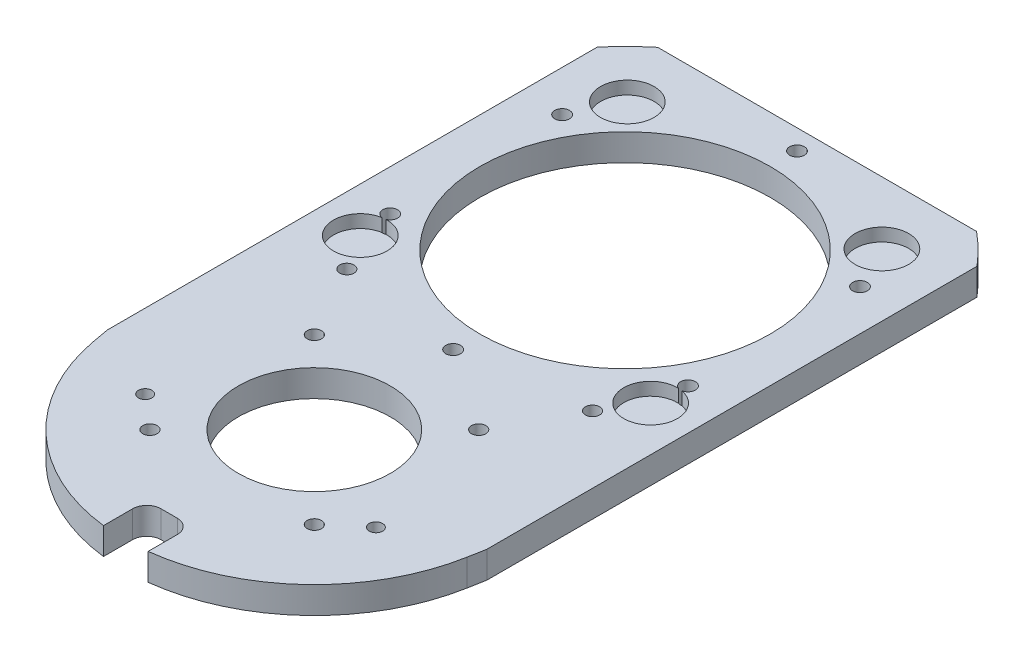
SolidWorks part; units mm, degrees
ref_plane "Front Plane" through (0, 0, 0) normal (0, 0, 1) x (1, 0, 0)
ref_plane "Top Plane" through (0, 0, 0) normal (0, 1, 0) x (1, 0, 0)
ref_plane "Right Plane" through (0, 0, 0) normal (1, 0, 0) x (0, 0, -1)
sketch "Sketch1" plane through (0, 0, 0) normal (0, 1, 0) x (1, 0, 0)
  line L0 (0, 0) -> (0, -69.5691) construction
  line L1 (0, 0) -> (0, -69.5691) construction
  line L2 (-42.5, -73.412) -> (-41.8107, -77.1925)
  line L3 (42.5, -73.412) -> (41.8107, -77.1925)
  line L4 (42.5, 36.2892) -> (42.5, -73.412)
  line L5 (-22.5, -47.0691) -> (22.5, -47.0691) construction
  line L6 (-35.6953, 43) -> (35.6953, 43)
  line L7 (-22.5, -47.0691) -> (-22.5, -92.0691) construction
  line L8 (-22.5, -92.0691) -> (22.5, -92.0691) construction
  line L9 (22.5, -47.0691) -> (22.5, -92.0691) construction
  line L10 (-22.5, -47.0691) -> (22.5, -92.0691) construction
  line L11 (-22.5, -92.0691) -> (22.5, -47.0691) construction
  line L12 (-42.5, 36.2892) -> (-42.5, -73.412)
  arc A0 (42.5, 36.2892) -> (35.6953, 43) centre (0, 0) ccw
  arc A1 (-41.8107, -77.1925) -> (41.8107, -77.1925) centre (0, -69.5691) ccw
  circle A2 centre (0, 0) radius 32.5
  circle A3 centre (0, -69.5691) radius 17
  arc A4 (-35.6953, 43) -> (-42.5, 36.2892) centre (0, 0) ccw
  point P1 (0, -34.7846)
  dimension "D1" = 65
  dimension "D2" = 34
  dimension "D7" = 85
  dimension "D3" = 69.5691
  dimension "D4" = 43
  dimension "D5" = 45
  dimension "D6" = 45
  dimension "D8" = 42.5
  dimension "D9" = 42.5
extrude "Boss-Extrude1" add sketch "Sketch1" along normal blind 6
sketch "Sketch2" plane through (0, 6, 0) normal (0, 1, 0) x (1, 0, 0)
  circle A0 centre (18.4, -51.1691) radius 1.6
  circle A1 centre (0, -69.5691) radius 17 construction
  dimension "D1" = 18.4
  dimension "D2" = 18.4
  dimension "D3" = 3.2
extrude "Cut-Extrude1" cut sketch "Sketch2" against normal blind 6
pattern_linear "LPattern1" count 2 spacing 36.8 along (0, 0, 1) count 2 spacing 36.8 along (-1, 0, 0) of "Cut-Extrude1"
sketch "Sketch3" plane through (0, 6, 0) normal (0, 1, 0) x (1, 0, 0)
  circle A0 centre (0, 38.5) radius 1.65
  dimension "D1" = 3.3
  dimension "D2" = 38.5
extrude "Cut-Extrude2" cut sketch "Sketch3" against normal blind 10
pattern_circular "CirPattern1" count 6 over 360 about axis through (0, 0, 0) along (0, 1, 0) of "Cut-Extrude2"
sketch "Sketch4" plane through (0, 6, 0) normal (0, 1, 0) x (1, 0, 0)
  line L1 (-22.5, -47.0691) -> (22.5, -47.0691)
  line L2 (-22.5, -47.0691) -> (-22.5, -92.0691)
  line L3 (-22.5, -92.0691) -> (22.5, -92.0691)
  line L4 (22.5, -47.0691) -> (22.5, -92.0691)
  line L5 (-22.5, -47.0691) -> (22.5, -92.0691) construction
  line L6 (-22.5, -92.0691) -> (22.5, -47.0691) construction
  circle A0 centre (0, 0) radius 42.5
  point P3 (0, -69.5691)
  dimension "D1" = 45
  dimension "D2" = 45
sketch "Sketch6" plane through (0, 6, 0) normal (0, 1, 0) x (1, 0, 0)
  line L1 (-5, -102.0691) -> (5, -102.0691)
  line L2 (-5, -102.0691) -> (-5, -122.0691)
  line L3 (-5, -122.0691) -> (5, -122.0691)
  line L4 (5, -102.0691) -> (5, -122.0691)
  line L5 (-5, -102.0691) -> (5, -122.0691) construction
  line L6 (-5, -122.0691) -> (5, -102.0691) construction
  arc A0 (-41.8107, -77.1925) -> (41.8107, -77.1925) centre (0, -69.5691) ccw construction
  point P0 (0, -112.0691)
  dimension "D1" = 10
  dimension "D2" = 10
extrude "Cut-Extrude4" cut sketch "Sketch6" against normal blind 10
sketch "Sketch7" plane through (0, 0, 0) normal (0, 1, 0) x (1, 0, 0)
  circle A0 centre (-27.5, -34.7846) radius 1.6
  circle A1 centre (-25.8298, -81.6138) radius 1.5
  circle A2 centre (25.8298, -81.6138) radius 1.5
  circle A3 centre (27.5, -34.7846) radius 1.6
extrude "Cut-Extrude5" cut sketch "Sketch7" along normal blind 20
fillet "Fillet1" radius 3.175 2 edges at (5, 3, 102.0691) (-5, 3, 102.0691)
sketch "Sketch8" plane through (0, 0, 0) normal (0, 1, 0) x (1, 0, 0)
  circle A0 centre (-28.5, 29) radius 6
  circle A1 centre (-32.5, -26.7846) radius 6
  circle A2 centre (32.5, -26.7846) radius 6
  circle A3 centre (28.5, 29) radius 6
  dimension "D1" = 12
  dimension "D2" = 12
  dimension "D3" = 12
  dimension "D4" = 12
extrude "Cut-Extrude6" cut sketch "Sketch8" along normal blind 20 from offset 3.1
equation "\"D3@LPattern1\"=2*18.4"
equation "\"D4@LPattern1\"=2*18.4"
equation "\"D4@Sketch1\"=\"D1@Sketch1\"/2+10.5"
equation "\"D8@Sketch1\"=85/2"
equation "\"D9@Sketch1\"=\"D8@Sketch1\""
equation "\"D2@Sketch5\"=\"D3@Sketch5\""
